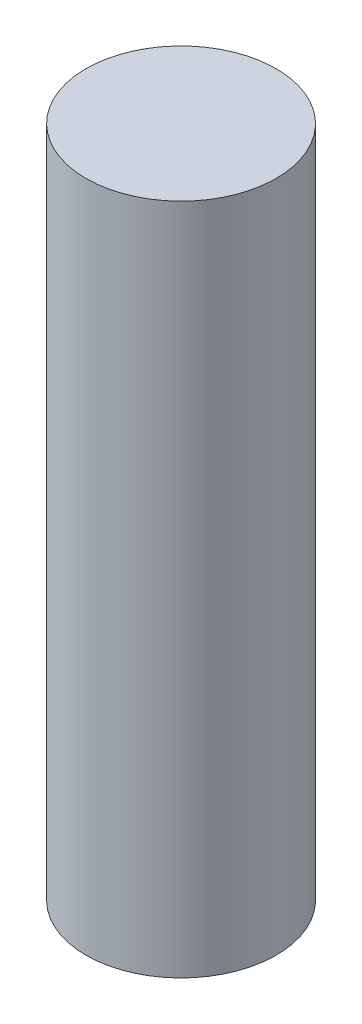
SolidWorks part; units mm, degrees
ref_plane "Front Plane" through (0, 0, 0) normal (0, 0, 1) x (1, 0, 0)
ref_plane "Top Plane" through (0, 0, 0) normal (0, 1, 0) x (1, 0, 0)
ref_plane "Right Plane" through (0, 0, 0) normal (1, 0, 0) x (0, 0, -1)
sketch "Sketch1" plane through (0, 0, 0) normal (0, 1, 0) x (1, 0, 0)
  circle A0 centre (0, 0) radius 9.165
  dimension "D1" = 18.33
extrude "Boss-Extrude1" add sketch "Sketch1" along normal mid plane 64.85
